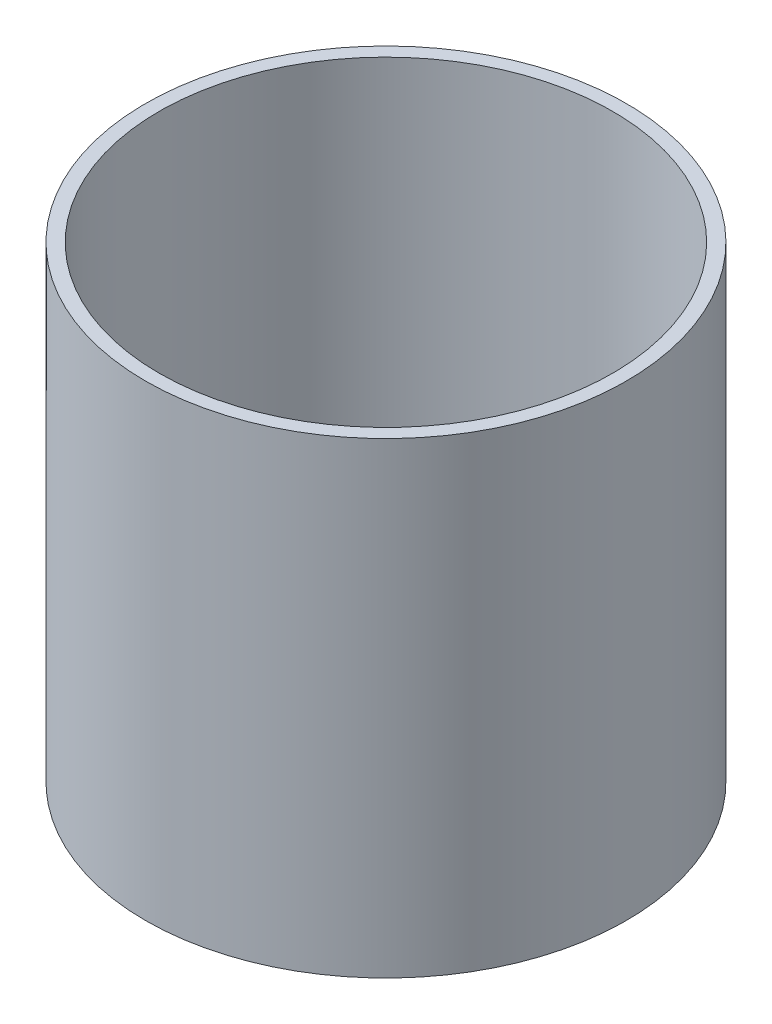
SolidWorks part; units mm, degrees
ref_plane "Front Plane" through (0, 0, 0) normal (0, 0, 1) x (1, 0, 0)
ref_plane "Top Plane" through (0, 0, 0) normal (0, 1, 0) x (1, 0, 0)
ref_plane "Right Plane" through (0, 0, 0) normal (1, 0, 0) x (0, 0, -1)
sketch "Sketch1" plane through (0, 0, 0) normal (0, 1, 0) x (1, 0, 0)
  circle A0 centre (-21.651, 19.0529) radius 53
extrude "Boss-Extrude1" add sketch "Sketch1" along normal blind 103
sketch "Sketch2" plane through (0, 103, 0) normal (0, 1, 0) x (1, 0, 0)
  circle A0 centre (-21.651, 19.0529) radius 50
extrude "Cut-Extrude1" cut sketch "Sketch2" against normal blind 100
